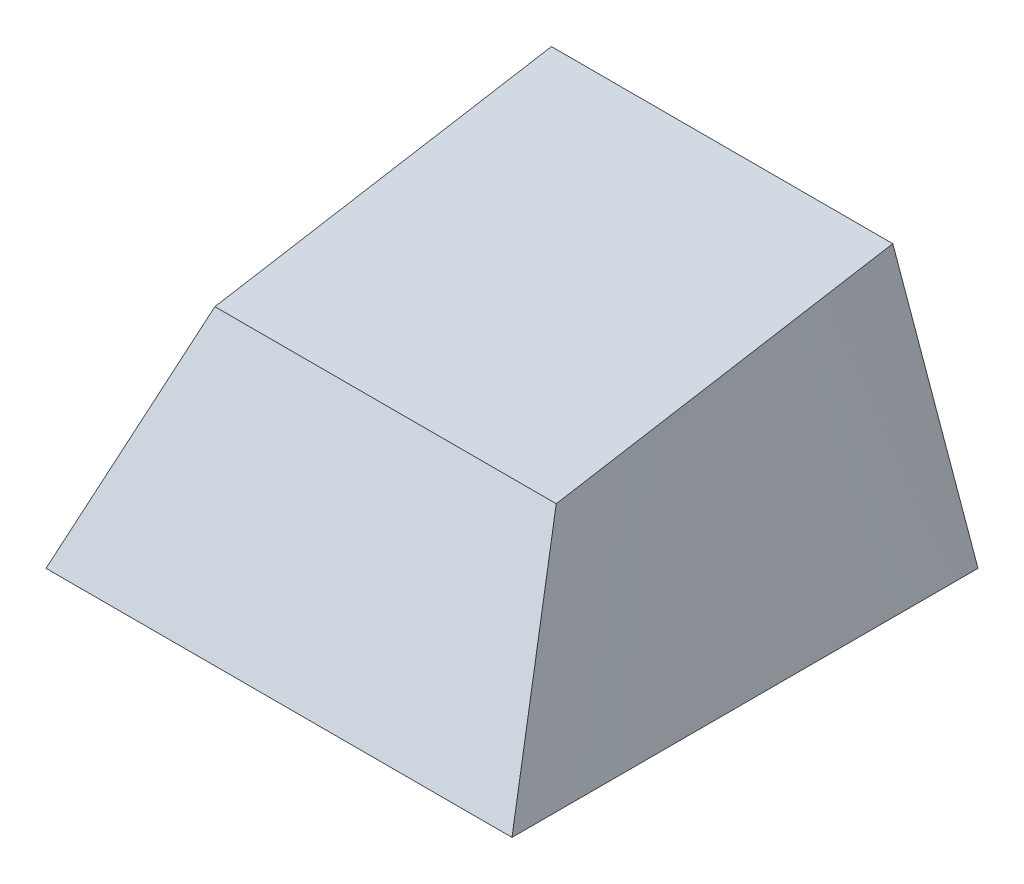
SolidWorks part; units mm, degrees
ref_plane "Front Plane" through (0, 0, 0) normal (0, 0, 1) x (1, 0, 0)
ref_plane "Top Plane" through (0, 0, 0) normal (0, 1, 0) x (1, 0, 0)
ref_plane "Right Plane" through (0, 0, 0) normal (1, 0, 0) x (0, 0, -1)
sketch "Sketch1" plane through (0, 0, 0) normal (0, 1, 0) x (1, 0, 0)
  line L1 (-9, 9) -> (9, 9)
  line L2 (-9, 9) -> (-9, -9)
  line L3 (-9, -9) -> (9, -9)
  line L4 (9, 9) -> (9, -9)
  point P4 (9, 0)
  point P6 (0, 9)
  dimension "D1" = 18
sketch "Sketch2" plane through (0, 0, 0) normal (1, 0, 0) x (0, 0, -1)
  line L0 (-4.8836, 7.9) -> (8.1164, 10.1)
  line L2 (9, 0) -> (-9, 0) construction
  line L3 (9, 0) -> (-9, 0) construction
  line L4 (8.1164, 10.1) -> (9, 0) construction
  point P2 (7.5314, 10.1)
  point P7 (0, 0)
  dimension "D1" = 7.9
  dimension "D2" = 10.1
  dimension "D3" = 13
  dimension "D4" = 5
ref_plane "Plane1" through (0, 8.4835, 1.4357) normal (0, 0.986, 0.1669) x (0, 0.1669, -0.986)
sketch "Sketch3" plane through (0, 8.4835, 1.4357) normal (0, 0.986, 0.1669) x (0, 0.1669, -0.986)
  line L1 (-3.497, 6.5924) -> (9.6878, 6.5924)
  line L2 (-3.497, 6.5924) -> (-3.497, -6.5924)
  line L3 (-3.497, -6.5924) -> (9.6878, -6.5924)
  line L4 (9.6878, 6.5924) -> (9.6878, -6.5924)
  point P4 (9.6878, 0)
loft "Loft1" add profiles "Sketch1", "Sketch3"
shell "Shell1" thickness 1.6
sketch "Sketch4" plane through (0, 0, 0) normal (0, -1, 0) x (1, 0, 0)
  line L0 (0, 0) -> (0, 9) construction
  line L2 (0, 0) -> (9, 0) construction
  line L3 (-9, 9) -> (9, 9) construction
  line L4 (9, -9) -> (9, 9) construction
  circle A0 centre (0, 0) radius 1.5
  point P4 (0, 0)
  point P6 (0, 0)
  point P8 (0, 0)
  point P9 (7.3436, 0)
  point P10 (7.3452, -1.0418)
  point P11 (0, 0)
  point P12 (0, 0)
  dimension "D1" = 3
extrude "Boss-Extrude1" add sketch "Sketch4" against normal up to surface (5.3576 mm away) from offset 2 offset against normal yes
sketch "Sketch5" plane through (0, 2, 0) normal (0, -1, 0) x (1, 0, 0)
  line L1 (-0.5, 1.25) -> (0.5, 1.25)
  line L2 (-0.5, 1.25) -> (-0.5, -1.25)
  line L3 (-0.5, -1.25) -> (0.5, -1.25)
  line L4 (0.5, 1.25) -> (0.5, -1.25)
  line L5 (-1.25, 0.5) -> (1.25, 0.5)
  line L6 (-1.25, 0.5) -> (-1.25, -0.5)
  line L7 (-1.25, -0.5) -> (1.25, -0.5)
  line L8 (1.25, 0.5) -> (1.25, -0.5)
  point P8 (0, 0.5)
  point P10 (1.25, 0)
  point P11 (0, 1.25)
  point P12 (0.5, 0)
  dimension "D1" = 1
  dimension "D2" = 2.5
extrude "Cut-Extrude1" cut sketch "Sketch5" against normal offset from surface (4.512 mm away) 0.5 contours L6 L7 L2 L5 | L2 L7 L4 L5 | L2 L5 L4 L1 | L8 L5 L4 L7 | L7 L2 L3 L4
